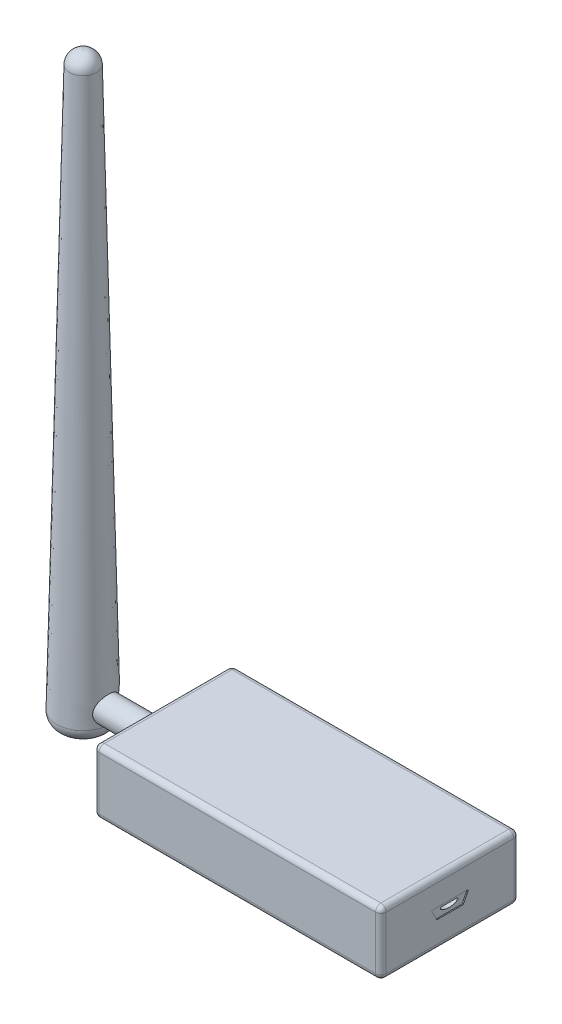
SolidWorks part; units mm, degrees
ref_plane "Front Plane" through (0, 0, 0) normal (0, 0, 1) x (1, 0, 0)
ref_plane "Top Plane" through (0, 0, 0) normal (0, 1, 0) x (1, 0, 0)
ref_plane "Right Plane" through (0, 0, 0) normal (1, 0, 0) x (0, 0, -1)
sketch "Sketch1" plane through (0, 0, 0) normal (0, 0, 1) x (1, 0, 0)
  line L0 (0, 0) -> (0, 110)
  line L1 (0, 0) -> (5, 0)
  line L2 (0, 110) -> (2.5, 110)
  line L3 (5, 0) -> (2.5, 110)
revolve "Revolve1" add sketch "Sketch1" angle 360 about L0
fillet "Fillet1" radius 2.5 2 edges at (0, 0, -5) (0, 110, -2.5)
sketch "Sketch2" plane through (0, 0, 0) normal (1, 0, 0) x (0, 0, -1)
  circle A0 centre (0, 5) radius 2.4432
extrude "Boss-Extrude1" add sketch "Sketch2" along normal blind 15
sketch "Sketch3" plane through (15, 0, 0) normal (1, 0, 0) x (0, 0, -1)
  line L1 (-13, -1) -> (13, -1)
  line L2 (-13, -1) -> (-13, 11)
  line L3 (-13, 11) -> (13, 11)
  line L4 (13, -1) -> (13, 11)
  line L5 (0, 11) -> (0, -1) construction
  line L6 (-13, 5) -> (13, 5) construction
  point P0 (0, 5)
extrude "Boss-Extrude2" add sketch "Sketch3" along normal blind 54
fillet "Fillet2" radius 1 12 edges at (42, 11, 13) (69, 5, 13) (42, -1, 13) (15, 5, 13) (15, 11, 0) (15, 5, -13) (15, -1, 0) (69, 5, -13) (42, -1, -13) (42, 11, -13) (69, -1, 0) (69, 11, 0)
sketch "Sketch6" plane through (69, 0, 0) normal (1, 0, 0) x (0, 0, -1)
  line L0 (-3.1764, 6) -> (3.1764, 6)
  line L9 (-2.5553, 4.1106) -> (-3.3553, 5.7106)
  line L10 (3.3553, 5.7106) -> (2.5553, 4.1106)
  line L11 (-2.3764, 4) -> (2.3764, 4)
  arc A0 (3.3553, 5.7106) -> (3.1764, 6) centre (3.1764, 5.8) ccw
  arc A1 (2.3764, 4) -> (2.5553, 4.1106) centre (2.3764, 4.2) ccw
  arc A2 (-2.5553, 4.1106) -> (-2.3764, 4) centre (-2.3764, 4.2) ccw
  arc A3 (-3.3553, 5.7106) -> (-3.1764, 6) centre (-3.1764, 5.8) cw
  point P8 (3.5, 6)
  point P12 (2.5, 4)
  point P15 (-2.5, 4)
  point P18 (-3.5, 6)
  dimension "D1" = 0.2
extrude "Cut-Extrude3" cut sketch "Sketch6" against normal blind 0.2
sketch "Sketch8" plane through (68.8, 0, 0) normal (1, 0, 0) x (0, 0, -1)
  line L0 (0.0477, 5.472) -> (1.486, 5.472)
  line L1 (0.0477, 5.472) -> (-1.3906, 5.472)
  arc A0 (-1.5, 5.1046) -> (1.5954, 5.1046) centre (0.0477, 7.472) ccw
  arc A1 (1.5954, 5.1046) -> (1.486, 5.472) centre (1.486, 5.272) ccw
  arc A2 (-1.5, 5.1046) -> (-1.3906, 5.472) centre (-1.3906, 5.272) cw
  dimension "D1" = 0.2
extrude "Cut-Extrude4" cut sketch "Sketch8" against normal blind 5
